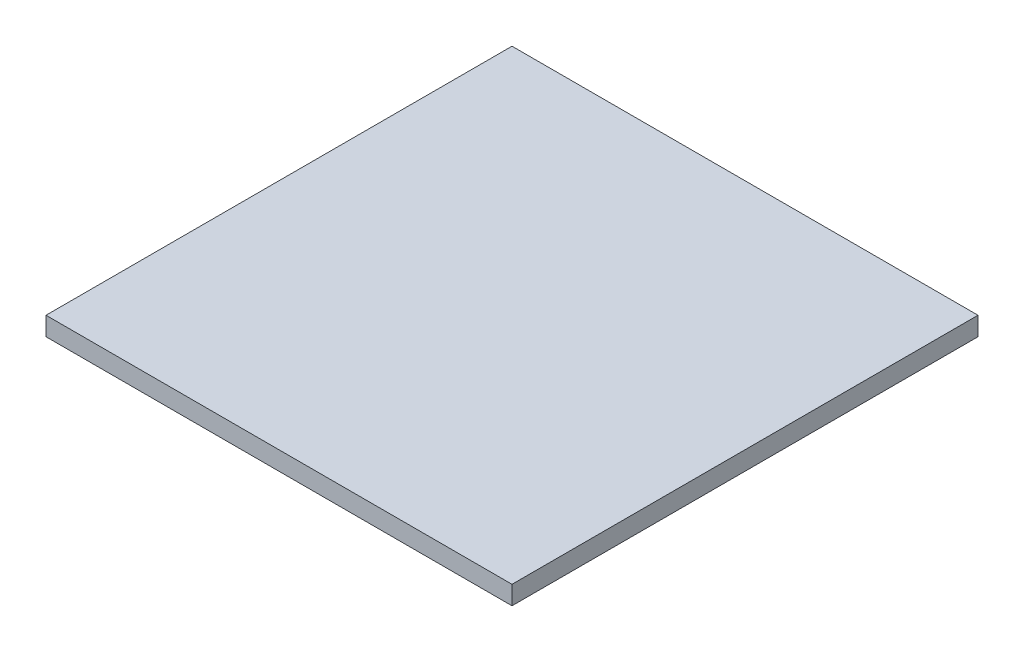
SolidWorks part; units mm, degrees
ref_plane "Front Plane" through (0, 0, 0) normal (0, 0, 1) x (1, 0, 0)
ref_plane "Top Plane" through (0, 0, 0) normal (0, 1, 0) x (1, 0, 0)
ref_plane "Right Plane" through (0, 0, 0) normal (1, 0, 0) x (0, 0, -1)
sketch "Sketch1" plane through (0, 0, 0) normal (0, 1, 0) x (1, 0, 0)
  line L1 (-76.8316, 179.9188) -> (173.1684, 179.9188)
  line L2 (-76.8316, 179.9188) -> (-76.8316, -70.0812)
  line L3 (-76.8316, -70.0812) -> (173.1684, -70.0812)
  line L4 (173.1684, 179.9188) -> (173.1684, -70.0812)
extrude "Boss-Extrude1" add sketch "Sketch1" along normal blind 10
sketch "Sketch2" plane through (0, 10, 0) normal (0, 1, 0) x (1, 0, 0)
  line L0 (48.1684, 179.9188) -> (48.1684, -70.0812) construction
  line L1 (173.1684, 179.9188) -> (-76.8316, 179.9188) construction
  line L2 (-76.8316, -70.0812) -> (173.1684, -70.0812) construction
  line L3 (-76.8316, 54.9188) -> (173.1684, 54.9188) construction
  line L4 (-76.8316, 179.9188) -> (-76.8316, -70.0812) construction
  line L5 (173.1684, -70.0812) -> (173.1684, 179.9188) construction
  line L11 (-26.8316, 129.9188) -> (123.1684, 129.9188) construction
  line L12 (-26.8316, 129.9188) -> (-26.8316, -20.0812) construction
  line L13 (-26.8316, -20.0812) -> (123.1684, -20.0812) construction
  line L14 (123.1684, 129.9188) -> (123.1684, -20.0812) construction
  circle A2 centre (48.1684, 149.9188) radius 4.4686 construction
  circle A3 centre (130.4409, 7.4188) radius 4.4686 construction
  circle A4 centre (-34.104, 7.4188) radius 4.4686 construction
  point P25 (48.1684, 54.9188)
  dimension "D3" = 20
  dimension "D4" = 3
  dimension "D1" = 75
  dimension "D2" = 75
